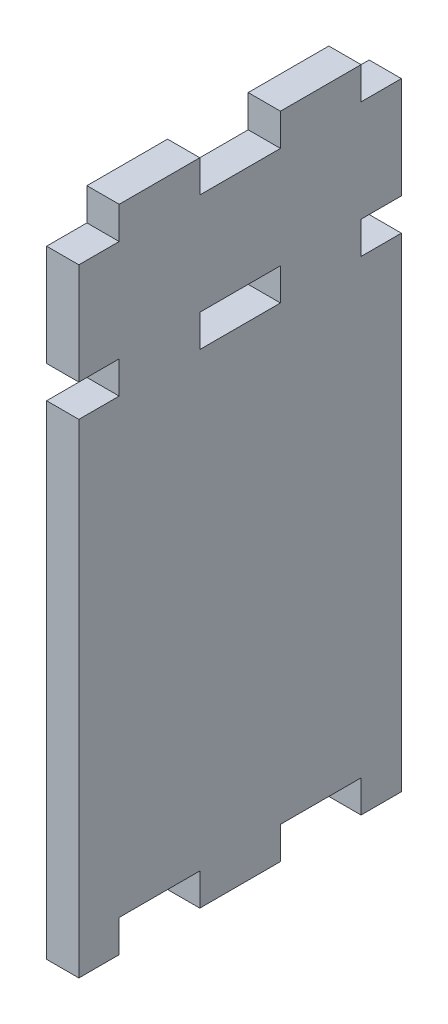
SolidWorks part; units mm, degrees
ref_plane "Front Plane" through (0, 0, 0) normal (0, 0, 1) x (1, 0, 0)
ref_plane "Top Plane" through (0, 0, 0) normal (0, 1, 0) x (1, 0, 0)
ref_plane "Right Plane" through (0, 0, 0) normal (1, 0, 0) x (0, 0, -1)
sketch "Sketch1" plane through (0, 0, 0) normal (1, 0, 0) x (0, 0, -1)
  line L0 (-7.5, 3.15) -> (-7.5, 5.15)
  line L1 (-10, 3.15) -> (-7.5, 3.15)
  line L2 (-10, 3.15) -> (-10, -3.15)
  line L3 (-10, -3.15) -> (-7.5, -3.15)
  line L4 (10, 3.15) -> (10, -3.15)
  line L5 (-10, 3.15) -> (10, -3.15) construction
  line L6 (-10, -3.15) -> (10, 3.15) construction
  line L7 (-7.5, 5.15) -> (-2.5, 5.15)
  line L8 (-2.5, 5.15) -> (-2.5, 3.15)
  line L9 (2.5, 3.15) -> (2.5, 5.15)
  line L10 (2.5, 5.15) -> (7.5, 5.15)
  line L11 (7.5, 5.15) -> (7.5, 3.15)
  line L12 (-2.5, 3.15) -> (2.5, 3.15)
  line L13 (7.5, 3.15) -> (10, 3.15)
  line L14 (-7.5, -3.15) -> (-7.5, -5.15)
  line L15 (-7.5, -5.15) -> (-2.5, -5.15)
  line L16 (-2.5, -5.15) -> (-2.5, -3.15)
  line L17 (7.5, -3.15) -> (7.5, -5.15)
  line L18 (7.5, -5.15) -> (2.5, -5.15)
  line L19 (2.5, -5.15) -> (2.5, -3.15)
  line L20 (-2.5, -3.15) -> (2.5, -3.15)
  line L21 (7.5, -3.15) -> (10, -3.15)
  point P0 (0, 0)
  point P12 (-5, 5.15)
  point P15 (5, 5.15)
  dimension "D1" = 6.3
  dimension "D2" = 20
  dimension "D3" = 5
  dimension "D4" = 2
  dimension "D5" = 5
  dimension "D6" = 5
  dimension "D7" = 2
  dimension "D8" = 5
  dimension "D9" = 2
  dimension "D10" = 2
extrude "Boss-Extrude1" add sketch "Sketch1" along normal blind 2
sketch "Sketch2" plane through (2, 0, 0) normal (1, 0, 0) x (0, 0, -1)
  line L0 (-10, 3.15) -> (-10, -7.6102) construction
  line L1 (-2.5, -5.15) -> (-12.7287, -5.15) construction
  line L2 (-10, -5.15) -> (10, -5.15)
  line L3 (-10, -5.15) -> (-10, -35.15)
  line L4 (10, -5.15) -> (10, -35.15)
  line L5 (-10, -35.15) -> (-7.5, -35.15)
  line L6 (-7.5, -35.15) -> (-7.5, -33.15)
  line L7 (-7.5, -33.15) -> (-2.5, -33.15)
  line L8 (-2.5, -33.15) -> (-2.5, -35.15)
  line L9 (7.5, -35.15) -> (7.5, -33.15)
  line L10 (7.5, -33.15) -> (2.5, -33.15)
  line L11 (2.5, -33.15) -> (2.5, -35.15)
  line L12 (-2.5, -35.15) -> (2.5, -35.15)
  line L13 (7.5, -35.15) -> (10, -35.15)
  point P6 (-10, -5.15)
  dimension "D1" = 30
  dimension "D2" = 2
extrude "Boss-Extrude2" add sketch "Sketch2" against normal blind 2
